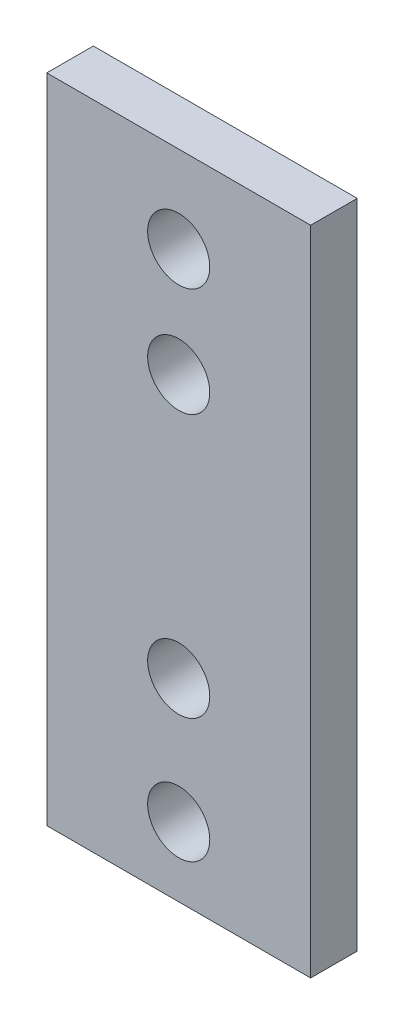
SolidWorks part; units mm, degrees
ref_plane "前基準面" through (0, 0, 0) normal (0, 0, 1) x (1, 0, 0)
ref_plane "上基準面" through (0, 0, 0) normal (0, 1, 0) x (1, 0, 0)
ref_plane "右基準面" through (0, 0, 0) normal (1, 0, 0) x (0, 0, -1)
sketch "草圖1" plane through (0, 0, 0) normal (0, 0, 1) x (1, 0, 0)
  line L1 (-14.3475, 15.5355) -> (2.6525, 15.5355)
  line L2 (-14.3475, 15.5355) -> (-14.3475, -26.4645)
  line L3 (-14.3475, -26.4645) -> (2.6525, -26.4645)
  line L4 (2.6525, 15.5355) -> (2.6525, -26.4645)
  circle A0 centre (-5.8475, 9.9539) radius 2
  circle A1 centre (-5.8475, 2.9539) radius 2
  circle A2 centre (-5.8475, -14.0035) radius 2
  circle A3 centre (-5.8475, -22.0035) radius 2
  dimension "D3" = 4
  dimension "D4" = 4
  dimension "D7" = 4
  dimension "D8" = 4
  dimension "D1" = 17
  dimension "D2" = 42
  dimension "D5" = 8
  dimension "D6" = 8.5
  dimension "D9" = 7
  dimension "D10" = 8.5
extrude "填料-伸長1" add sketch "草圖1" along normal blind 3
